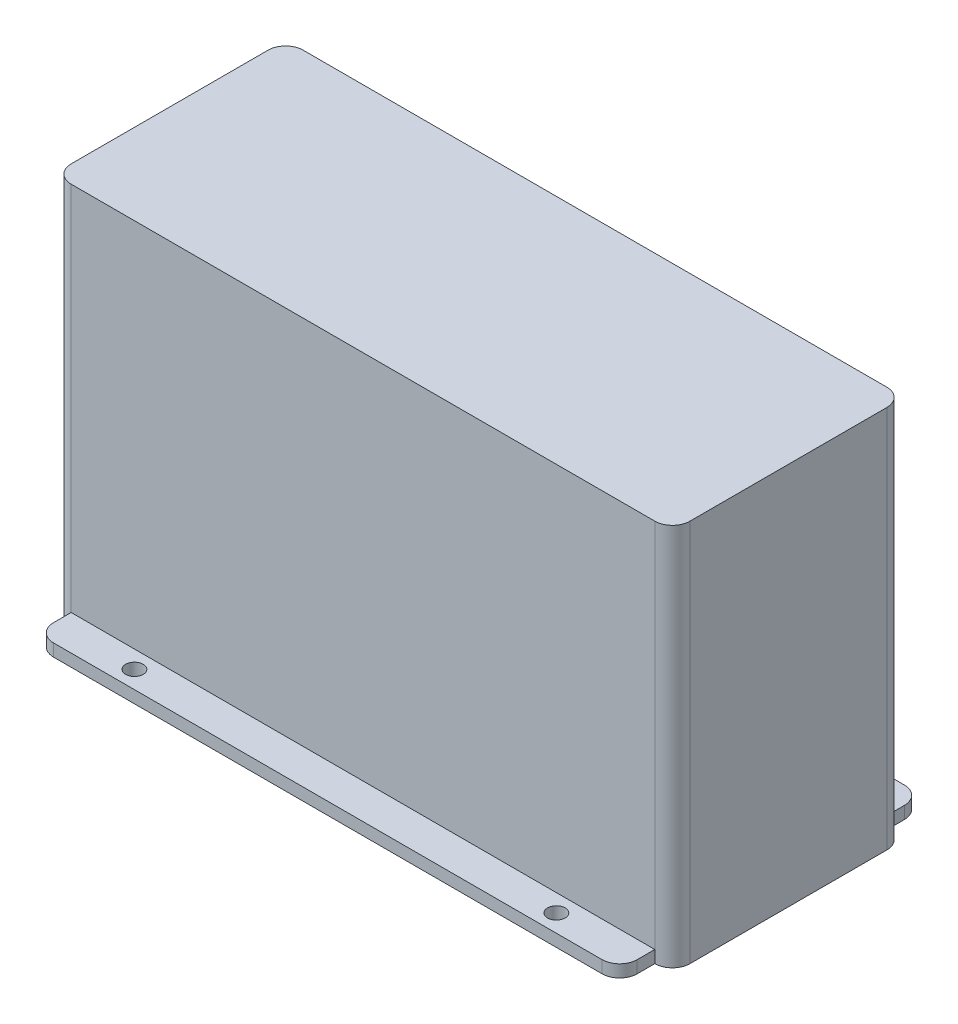
SolidWorks part; units mm, degrees
ref_plane "Front Plane" through (0, 0, 0) normal (0, 0, 1) x (1, 0, 0)
ref_plane "Top Plane" through (0, 0, 0) normal (0, 1, 0) x (1, 0, 0)
ref_plane "Right Plane" through (0, 0, 0) normal (1, 0, 0) x (0, 0, -1)
sketch "Sketch1" plane through (0, 0, 0) normal (0, 1, 0) x (1, 0, 0)
  line L1 (80, -30) -> (-80, -30)
  line L2 (85, -25) -> (85, 25)
  line L3 (80, 30) -> (-80, 30)
  line L4 (-85, -25) -> (-85, 25)
  line L5 (85, -30) -> (-85, 30) construction
  line L6 (85, 30) -> (-85, -30) construction
  line L7 (83, -33) -> (-83, -33)
  line L8 (88, -28) -> (88, 28)
  line L9 (83, 33) -> (-83, 33)
  line L10 (-88, -28) -> (-88, 28)
  line L11 (88, -33) -> (-88, 33) construction
  line L12 (88, 33) -> (-88, -33) construction
  arc A0 (83, 33) -> (88, 28) centre (83, 28) cw
  arc A1 (80, 30) -> (85, 25) centre (80, 25) cw
  arc A2 (83, -33) -> (88, -28) centre (83, -28) ccw
  arc A3 (80, -30) -> (85, -25) centre (80, -25) ccw
  arc A4 (-80, -30) -> (-85, -25) centre (-80, -25) cw
  arc A5 (-83, -33) -> (-88, -28) centre (-83, -28) cw
  arc A6 (-83, 33) -> (-88, 28) centre (-83, 28) ccw
  arc A7 (-85, 25) -> (-80, 30) centre (-80, 25) cw
  point P0 (0, 0)
  point P6 (0, 0)
  dimension "D5" = 5
  dimension "D1" = 60
  dimension "D2" = 170
  dimension "D3" = 3
  dimension "D4" = 3
extrude "Boss-Extrude1" add sketch "Sketch1" along normal blind 106
sketch "Sketch2" plane through (0, 106, 0) normal (0, 1, 0) x (1, 0, 0)
  line L1 (-83, 33) -> (83, 33)
  line L2 (-88, 28) -> (-88, -28)
  line L3 (-83, -33) -> (83, -33)
  line L4 (88, 28) -> (88, -28)
  arc A0 (-88, -28) -> (-83, -33) centre (-83, -28) ccw
  arc A1 (83, -33) -> (88, -28) centre (83, -28) ccw
  arc A2 (88, 28) -> (83, 33) centre (83, 28) ccw
  arc A3 (-83, 33) -> (-88, 28) centre (-83, 28) ccw
  dimension "D1" = 5
extrude "Boss-Extrude2" add sketch "Sketch2" along normal blind 3
sketch "Sketch3" plane through (0, 0, 0) normal (0, -1, 0) x (1, 0, 0)
  line L0 (0, -55) -> (0, 55) construction
  line L1 (-83, 33) -> (83, 33)
  line L2 (-83, 33) -> (-83, 38)
  line L3 (-78, 43) -> (78, 43)
  line L4 (83, 33) -> (83, 38)
  circle A0 centre (-60, 38) radius 2.5
  circle A1 centre (60, 38) radius 2.5
  arc A2 (78, 43) -> (83, 38) centre (78, 38) cw
  arc A3 (-78, 43) -> (-83, 38) centre (-78, 38) ccw
  point P16 (83, 43)
  dimension "D2" = 60
  dimension "D5" = 5
  dimension "D1" = 10
  dimension "D3" = 0
  dimension "D4" = 0
extrude "Boss-Extrude3" add sketch "Sketch3" against normal blind 3.5
mirror "Mirror1" about plane through (0, 0, 0) normal (0, 0, 1) of "Boss-Extrude3"
sketch "Sketch4" plane through (0, 0, -33) normal (0, 0, -1) x (-1, 0, 0)
  line L1 (47.5, -56) -> (-47.5, -56)
  line L2 (47.5, -56) -> (47.5, 51)
  line L3 (42.5, 56) -> (-42.5, 56)
  line L4 (-47.5, -56) -> (-47.5, 51)
  line L5 (47.5, -56) -> (-47.5, 56) construction
  line L6 (47.5, 56) -> (-47.5, -56) construction
  arc A0 (47.5, 51) -> (42.5, 56) centre (42.5, 51) ccw
  arc A1 (-42.5, 56) -> (-47.5, 51) centre (-42.5, 51) ccw
  point P0 (0, 0)
  dimension "D3" = 5
  dimension "D1" = 95
  dimension "D2" = 112
extrude "Cut-Extrude1" cut sketch "Sketch4" against normal mid plane 33
fillet "Fillet1" radius 5 2 edges at (-47.5, 1.75, -43) (47.5, 1.75, -43)
